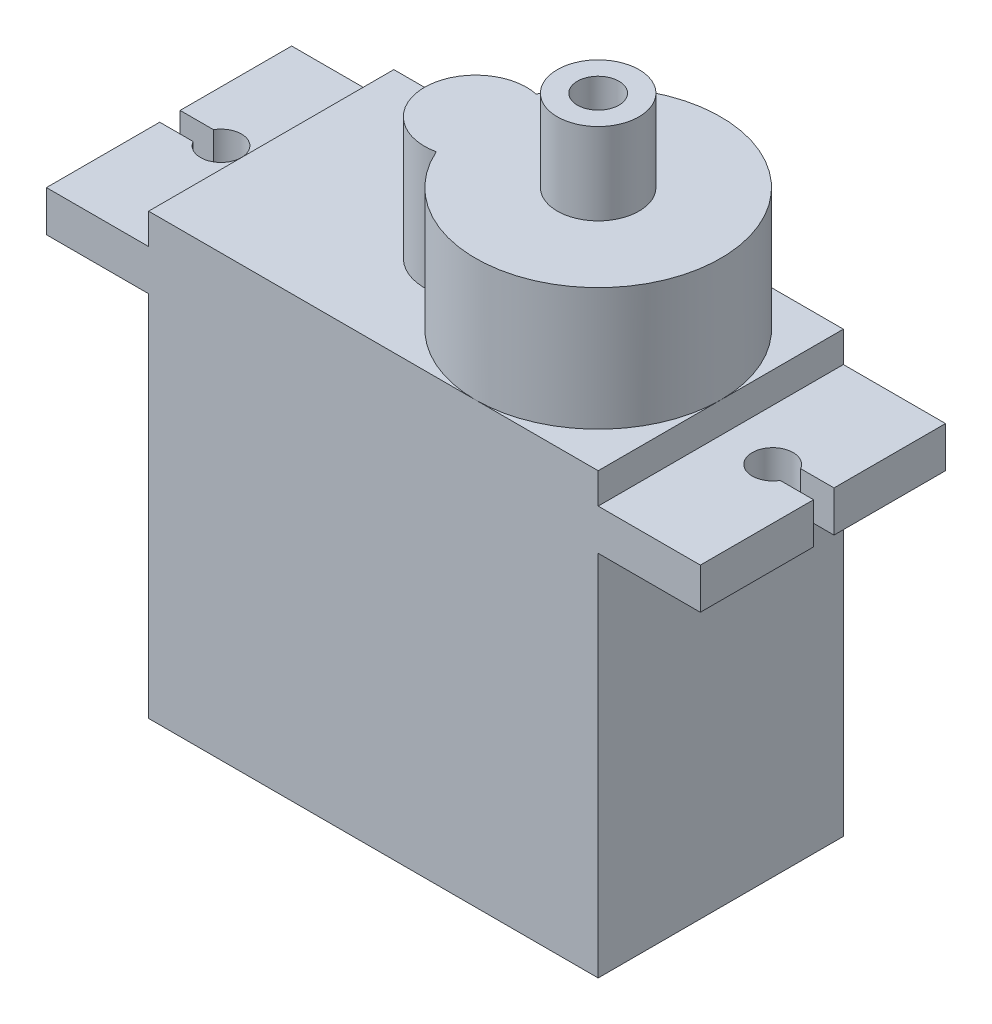
SolidWorks part; units mm, degrees
ref_plane "前视基准面" through (0, 0, 0) normal (0, 0, 1) x (1, 0, 0)
ref_plane "上视基准面" through (0, 0, 0) normal (0, 1, 0) x (1, 0, 0)
ref_plane "右视基准面" through (0, 0, 0) normal (1, 0, 0) x (0, 0, -1)
sketch "草图1" plane through (0, 0, 0) normal (0, 0, 1) x (1, 0, 0)
  line L0 (-11, 12.5368) -> (-16, 12.5368)
  line L1 (11, -5.4632) -> (-11, -5.4632)
  line L2 (11, -5.4632) -> (11, 12.5368)
  line L4 (-11, -5.4632) -> (-11, 12.5368)
  line L5 (-11, 14.5368) -> (-16, 14.5368)
  line L6 (11, 16.0368) -> (-11, 16.0368)
  line L7 (16, 14.5368) -> (11, 14.5368)
  line L8 (16, 14.5368) -> (16, 12.5368)
  line L9 (16, 12.5368) -> (11, 12.5368)
  line L10 (-16, 14.5368) -> (-16, 12.5368)
  line L11 (11, 16.0368) -> (11, 14.5368)
  line L13 (-11, 16.0368) -> (-11, 14.5368)
  point P0 (0, 0)
  point P6 (0, 10)
  point P11 (0, 15.2868)
  dimension "D1" = 22
  dimension "D2" = 18
  dimension "D3" = 32
  dimension "D4" = 5
  dimension "D5" = 2
  dimension "D7" = 1.5
extrude "凸台-拉伸1" add sketch "草图1" along normal blind 12
ref_plane "基准面4" through (0, 16.0368, 0) normal (0, 1, 0) x (1, 0, 0)
sketch "草图2" plane through (0, 16.0368, 0) normal (0, 1, 0) x (1, 0, 0)
  line L0 (11, 0) -> (-11, 0) construction
  line L1 (11, -12) -> (11, 0) construction
  arc A0 (-0.4792, -8.4451) -> (-0.4792, -3.5549) centre (5, -6) ccw
  arc A1 (-0.4792, -3.5549) -> (-0.4792, -8.4451) centre (-1, -6) ccw
  dimension "D1" = 12
  dimension "D4" = 5
  dimension "D2" = 6
  dimension "D3" = 6
extrude "凸台-拉伸3" add sketch "草图2" along normal blind 6
ref_plane "基准面6" through (0, 22.0368, 0) normal (0, 1, 0) x (1, 0, 0)
sketch "草图4" plane through (0, 22.0368, 0) normal (0, 1, 0) x (1, 0, 0)
  circle A1 centre (5, -6) radius 2
  arc A2 (-0.4792, -8.4451) -> (-0.4792, -3.5549) centre (5, -6) ccw construction
  dimension "D1" = 0
  dimension "D2" = 4
extrude "凸台-拉伸4" add sketch "草图4" along normal blind 4
ref_plane "基准面7" through (0, 14.5368, 0) normal (0, -1, 0) x (-1, 0, 0)
sketch "草图5" plane through (0, 14.5368, 0) normal (0, -1, 0) x (-1, 0, 0)
  line L0 (-16, -12) -> (-16, 0) construction
  line L1 (0, -1000) -> (0, 49000) construction
  line L2 (-14.366, -6.4583) -> (-16, -6.4583)
  line L4 (-14.366, -5.4583) -> (-16, -5.4583)
  line L5 (-16, -6.4583) -> (-16, -5.4583)
  line L6 (16, -6.4583) -> (16, -5.4583)
  line L7 (14.366, -5.4583) -> (16, -5.4583)
  line L8 (14.366, -6.4583) -> (16, -6.4583)
  arc A0 (-14.366, -6.4583) -> (-14.366, -5.4583) centre (-13.5, -5.9583) ccw
  arc A1 (14.366, -6.4583) -> (14.366, -5.4583) centre (13.5, -5.9583) cw
  point P4 (-14.5, -5.9583)
  point P16 (14.5, -5.9583)
  dimension "D1" = 2.5
  dimension "D2" = 1
extrude "切除-拉伸2" cut sketch "草图5" along normal through all
sketch "草图6" plane through (0, 26.0368, 0) normal (0, 1, 0) x (1, 0, 0)
  circle A0 centre (5, -6) radius 1.0176
extrude "切除-拉伸3" cut sketch "草图6" against normal through all
